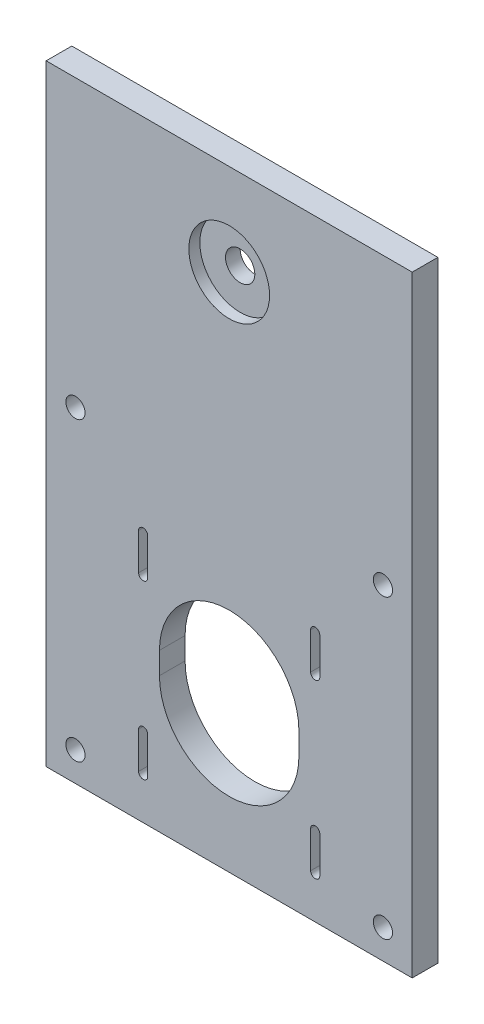
SolidWorks part; units mm, degrees
ref_plane "Front Plane" through (0, 0, 0) normal (0, 0, 1) x (1, 0, 0)
ref_plane "Top Plane" through (0, 0, 0) normal (0, 1, 0) x (1, 0, 0)
ref_plane "Right Plane" through (0, 0, 0) normal (1, 0, 0) x (0, 0, -1)
sketch "Sketch1" plane through (0, 0, 0) normal (0, 0, 1) x (1, 0, 0)
  line L1 (-50, 123.5) -> (50, 123.5)
  line L2 (-50, 123.5) -> (-50, -123.5)
  line L3 (-50, -123.5) -> (50, -123.5)
  line L4 (50, 123.5) -> (50, -123.5)
  line L5 (-50, 123.5) -> (50, -123.5) construction
  line L6 (-50, -123.5) -> (50, 123.5) construction
  line L8 (-19.05, -80.5) -> (-19.05, -86.5)
  line L9 (19.05, -86.5) -> (19.05, -80.5)
  line L10 (-23.5, -55) -> (-23.5, -65) construction
  line L14 (-22.25, -55) -> (-22.25, -65)
  line L15 (-24.75, -55) -> (-24.75, -65)
  line L16 (0, -83.5) -> (41.1398, -83.5) construction
  line L17 (0, -83.5) -> (0, -119.2312) construction
  line L18 (23.5, -55) -> (23.5, -65) construction
  line L19 (22.25, -55) -> (22.25, -65)
  line L20 (24.75, -55) -> (24.75, -65)
  line L21 (23.5, -112) -> (23.5, -102) construction
  line L22 (22.25, -112) -> (22.25, -102)
  line L23 (24.75, -112) -> (24.75, -102)
  line L24 (-23.5, -112) -> (-23.5, -102) construction
  line L25 (-22.25, -112) -> (-22.25, -102)
  line L26 (-24.75, -112) -> (-24.75, -102)
  circle A0 centre (-42, -34.5) radius 2.625
  circle A1 centre (42, -34.5) radius 2.625
  circle A2 centre (-42, -115.5) radius 2.625
  circle A3 centre (42, -115.5) radius 2.625
  arc A6 (19.05, -80.5) -> (-19.05, -80.5) centre (0, -80.5) ccw
  arc A7 (-19.05, -86.5) -> (19.05, -86.5) centre (0, -86.5) ccw
  arc A10 (-22.25, -55) -> (-24.75, -55) centre (-23.5, -55) ccw
  arc A11 (-24.75, -65) -> (-22.25, -65) centre (-23.5, -65) ccw
  arc A12 (22.25, -55) -> (24.75, -55) centre (23.5, -55) cw
  arc A13 (24.75, -65) -> (22.25, -65) centre (23.5, -65) cw
  arc A14 (22.25, -112) -> (24.75, -112) centre (23.5, -112) ccw
  arc A15 (24.75, -102) -> (22.25, -102) centre (23.5, -102) ccw
  arc A16 (-22.25, -112) -> (-24.75, -112) centre (-23.5, -112) cw
  arc A17 (-24.75, -102) -> (-22.25, -102) centre (-23.5, -102) cw
  circle A18 centre (0, 18.5) radius 4
  circle A19 centre (42, 115.5) radius 2.625
  circle A20 centre (-42, 115.5) radius 2.625
  circle A21 centre (-14, 32.5) radius 2.625 construction
  circle A22 centre (14, 32.5) radius 2.625 construction
  circle A23 centre (14, 4.5) radius 2.625 construction
  circle A24 centre (-14, 4.5) radius 2.625 construction
  point P0 (0, 0)
  point P14 (-23.5, -60)
  point P17 (0, -83.5)
  point P34 (23.5, -60)
  point P41 (23.5, -107)
  point P48 (-23.5, -107)
  dimension "D3" = 5.25
  dimension "D4" = 81
  dimension "D6" = 2.5
  dimension "D8" = 8
  dimension "D12" = 19.05
  dimension "D14" = 3
  dimension "D15" = 23.5
  dimension "D16" = 8
  dimension "D19" = 5.25
  dimension "D1" = 100
  dimension "D2" = 247
  dimension "D5" = 84
  dimension "D7" = 10
  dimension "D9" = 6
  dimension "D10" = 8
  dimension "D11" = 23.5
  dimension "D17" = 105
  dimension "D18" = 8
  dimension "D20" = 28
  dimension "D21" = 28
  dimension "D22" = 14
  dimension "D23" = 14
  dimension "D24" = 83.5
extrude "Boss-Extrude1" add sketch "Sketch1" along normal blind 7
sketch "Sketch2" plane through (0, 0, 7) normal (0, 0, 1) x (1, 0, 0)
  circle A0 centre (0, 18.5) radius 11.025
  dimension "D1" = 22.05
extrude "Cut-Extrude1" cut sketch "Sketch2" against normal blind 3
sketch "Sketch3" plane through (0, 0, 0) normal (0, 0, 1) x (1, 0, 0)
  line L0 (-23.5, -65) -> (-23.5, -55) construction
  line L1 (-26.5, -65) -> (-26.5, -55)
  line L2 (-20.5, -65) -> (-20.5, -55)
  line L3 (23.5, -65) -> (23.5, -55) construction
  line L4 (20.5, -65) -> (20.5, -55)
  line L5 (26.5, -65) -> (26.5, -55)
  line L6 (-23.5, -112) -> (-23.5, -102) construction
  line L7 (-26.5, -112) -> (-26.5, -102)
  line L8 (-20.5, -112) -> (-20.5, -102)
  line L9 (23.5, -112) -> (23.5, -102) construction
  line L10 (20.5, -112) -> (20.5, -102)
  line L11 (26.5, -112) -> (26.5, -102)
  arc A0 (-26.5, -65) -> (-20.5, -65) centre (-23.5, -65) ccw
  arc A1 (-20.5, -55) -> (-26.5, -55) centre (-23.5, -55) ccw
  arc A2 (20.5, -65) -> (26.5, -65) centre (23.5, -65) ccw
  arc A3 (26.5, -55) -> (20.5, -55) centre (23.5, -55) ccw
  arc A4 (-26.5, -112) -> (-20.5, -112) centre (-23.5, -112) ccw
  arc A5 (-20.5, -102) -> (-26.5, -102) centre (-23.5, -102) ccw
  arc A6 (20.5, -112) -> (26.5, -112) centre (23.5, -112) ccw
  arc A7 (26.5, -102) -> (20.5, -102) centre (23.5, -102) ccw
  point P4 (-23.5, -60)
  point P9 (23.5, -60)
  point P21 (-23.5, -107)
  point P29 (23.5, -107)
  dimension "D1" = 3
extrude "Cut-Extrude2" cut sketch "Sketch3" along normal blind 3
sketch "Sketch4" plane through (0, 0, 7) normal (0, 0, 1) x (1, 0, 0)
  line L0 (50, -123.5) -> (50, 123.5) construction
  line L1 (-50, 123.5) -> (50, 123.5)
  line L2 (-50, 123.5) -> (-50, 43.5)
  line L3 (-50, 43.5) -> (50, 43.5)
  line L4 (50, 123.5) -> (50, 43.5)
  line L5 (-50, 123.5) -> (50, 43.5) construction
  line L6 (-50, 43.5) -> (50, 123.5) construction
  line L7 (50, 123.5) -> (-50, 123.5) construction
  line L8 (-50, 123.5) -> (-50, -123.5) construction
  point P0 (0, 83.5)
  dimension "D1" = 80
extrude "Cut-Extrude3" cut sketch "Sketch4" against normal through all
